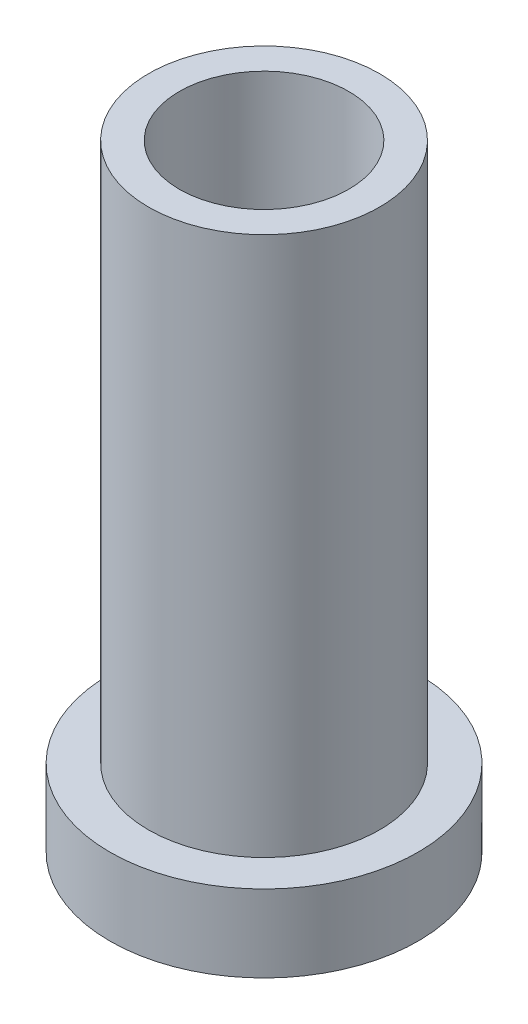
SolidWorks part; units mm, degrees
material "AISI 1010 Aço, barra laminada a quente"
ref_plane "Plano frontal" through (0, 0, 0) normal (0, 0, 1) x (1, 0, 0)
ref_plane "Plano superior" through (0, 0, 0) normal (0, 1, 0) x (1, 0, 0)
ref_plane "Plano direito" through (0, 0, 0) normal (1, 0, 0) x (0, 0, -1)
sketch "Esboço4" plane through (0, 0, 0) normal (0, 1, 0) x (1, 0, 0)
  circle A0 centre (0, 0) radius 10
  dimension "D1" = 20
extrude "Ressalto-extrusão3" add sketch "Esboço4" along normal blind 5
sketch "Esboço5" plane through (0, 5, 0) normal (0, 1, 0) x (1, 0, 0)
  circle A0 centre (0, 0) radius 7.5
  dimension "D1" = 15
extrude "Ressalto-extrusão4" add sketch "Esboço5" along normal blind 35
sketch "Esboço6" plane through (0, 40, 0) normal (0, 1, 0) x (1, 0, 0)
  circle A0 centre (0, 0) radius 5.5
  dimension "D1" = 11
extrude "Corte-extrusão2" cut sketch "Esboço6" against normal through all
